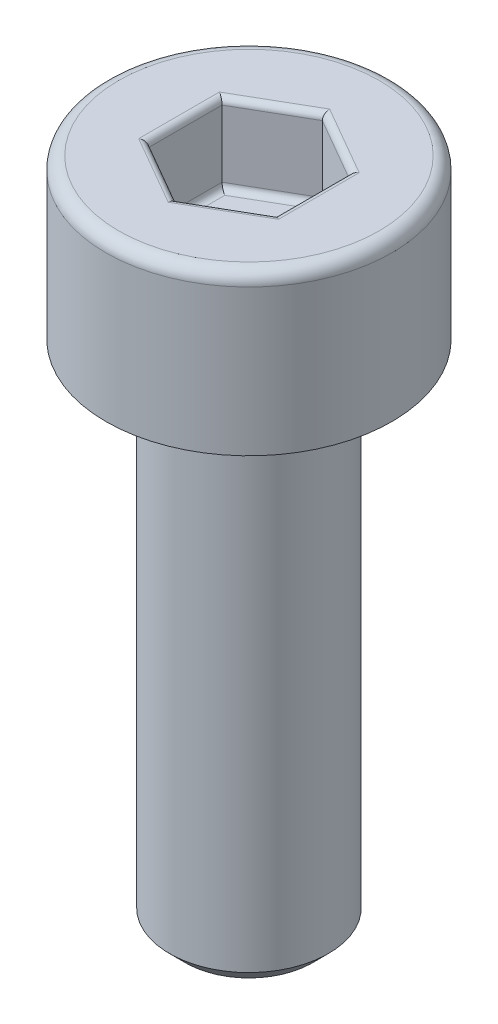
SolidWorks part; units mm, degrees
ref_plane "Front Plane" through (0, 0, 0) normal (0, 0, 1) x (1, 0, 0)
ref_plane "Top Plane" through (0, 0, 0) normal (0, 1, 0) x (1, 0, 0)
ref_plane "Right Plane" through (0, 0, 0) normal (1, 0, 0) x (0, 0, -1)
sketch "Sketch1" plane through (0, 0, 0) normal (0, 0, 1) x (1, 0, 0)
  line L0 (0, 0) -> (0, -47.0967) construction
  line L1 (0, -10.5) -> (-1.25, -10.5)
  line L2 (-1.25, -10.5) -> (-1.25, -2.5)
  line L3 (-1.25, -2.5) -> (-2.25, -2.5)
  line L4 (-2.25, -2.5) -> (-2.25, 0)
  line L5 (-2.25, 0) -> (0, 0)
  line L6 (0, 0) -> (0, -10.5)
  dimension "D1" = 8
  dimension "d" = 2.5
  dimension "k" = 2.5
  dimension "dk" = 4.5
revolve "Revolve1" add sketch "Sketch1" angle 360 about L0
chamfer "Chamfer1" distance 0.25 angle 45 2 edges at (0, -2.5, 1.25) (0, -10.5, 1.25)
fillet "Fillet1" radius 0.2 1 edges at (0, 0, 2.25)
sketch "Sketch2" plane through (0, 0, 0) normal (0, 1, 0) x (1, 0, 0)
  line L1 (0, 1.1547) -> (-1, 0.5774)
  line L2 (-1, 0.5774) -> (-1, -0.5774)
  line L3 (-1, -0.5774) -> (0, -1.1547)
  line L4 (0, -1.1547) -> (1, -0.5774)
  line L5 (1, -0.5774) -> (1, 0.5774)
  line L6 (1, 0.5774) -> (0, 1.1547)
  circle A0 centre (0, 0) radius 1 construction
  dimension "s" = 2
extrude "Cut-Extrude1" cut sketch "Sketch2" against normal blind 1.25
fillet "Fillet2" radius 0.1 12 edges at (-0.5, 0, -0.866) (-1, 0, 0) (-0.5, 0, 0.866) (0.5, 0, 0.866) (1, 0, 0) (0.5, 0, -0.866) (1, -1.25, 0) (0.5, -1.25, 0.866) (-0.5, -1.25, 0.866) (-1, -1.25, 0) (-0.5, -1.25, -0.866) (0.5, -1.25, -0.866)
